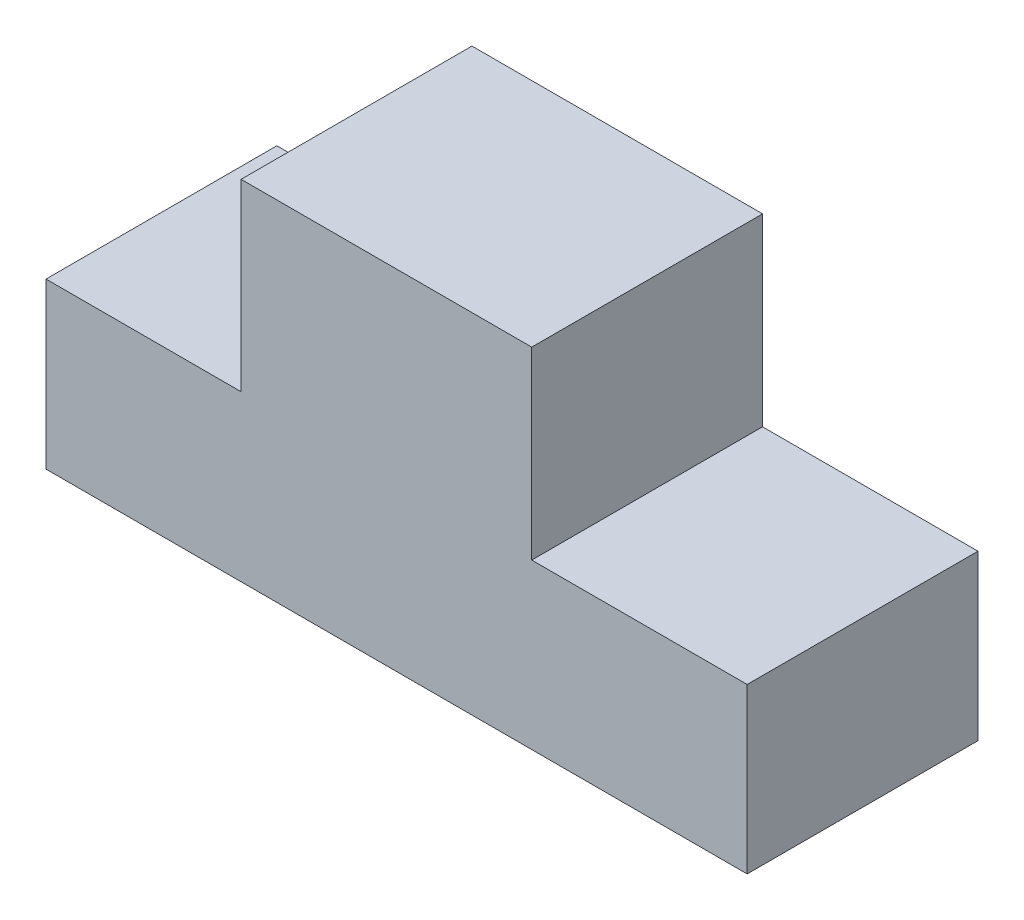
SolidWorks part; units mm, degrees
ref_plane "Ön Düzlem" through (0, 0, 0) normal (0, 0, 1) x (1, 0, 0)
ref_plane "Üst Düzlem" through (0, 0, 0) normal (0, 1, 0) x (1, 0, 0)
ref_plane "Sağ Düzlem" through (0, 0, 0) normal (1, 0, 0) x (0, 0, -1)
sketch "Çizim1" plane through (0, 0, 0) normal (0, 0, 1) x (1, 0, 0)
  line L0 (-58.1283, 67.9131) -> (48.8863, 67.9131)
  line L1 (48.8863, 0) -> (128.2118, 0)
  line L2 (128.2118, 0) -> (128.2118, -60.4295)
  line L3 (128.2118, -60.4295) -> (32.7967, -60.4295)
  line L4 (32.7967, -60.4295) -> (-37.1744, -60.4295)
  line L5 (-37.1744, -60.4295) -> (-129.9702, -60.4295)
  line L6 (-129.9702, -60.4295) -> (-129.9702, 0.1871)
  line L7 (-129.9702, 0.1871) -> (-58.1283, 0.1871)
  line L8 (-58.1283, 0.1871) -> (-58.1283, 67.9131)
  line L9 (48.8863, 67.9131) -> (48.8863, 0)
  point P7 (-37.1744, -60.4295)
extrude "Yükseklik-Ekstrüzyon1" add sketch "Çizim1" along normal blind 85
